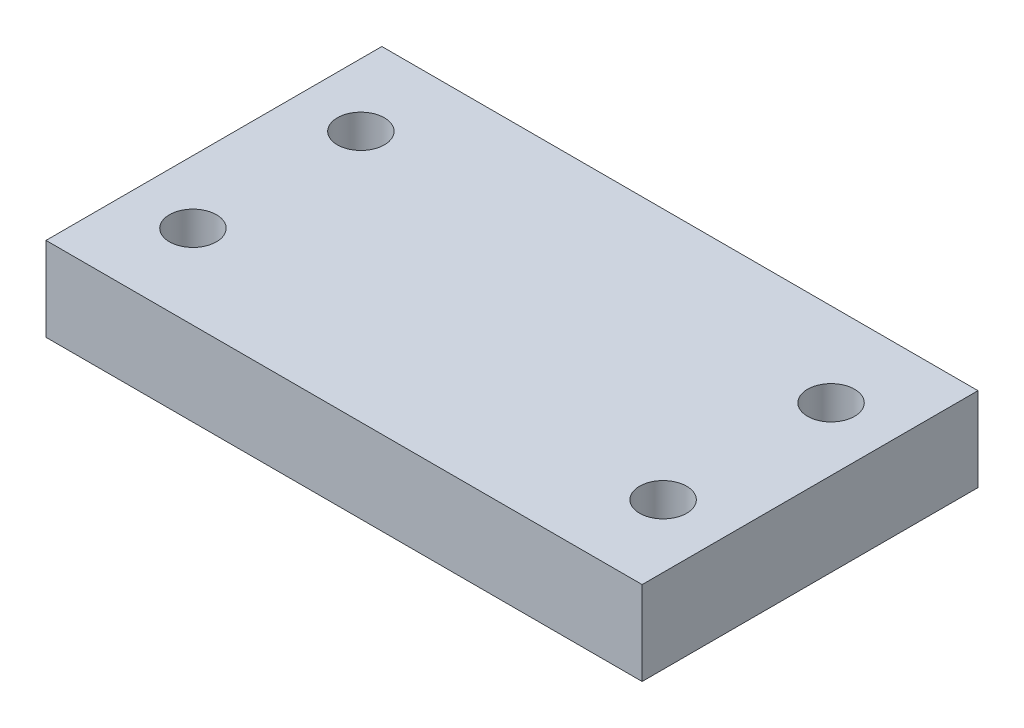
SolidWorks part; units mm, degrees
ref_plane "Front Plane" through (0, 0, 0) normal (0, 0, 1) x (1, 0, 0)
ref_plane "Top Plane" through (0, 0, 0) normal (0, 1, 0) x (1, 0, 0)
ref_plane "Right Plane" through (0, 0, 0) normal (1, 0, 0) x (0, 0, -1)
sketch "Sketch1" plane through (0, 0, 0) normal (0, 1, 0) x (1, 0, 0)
  line L0 (0, -55) -> (0, 55) construction
  line L2 (-35.5, -10) -> (-35.5, 10)
  line L4 (35.5, -10) -> (35.5, 10)
  line L5 (-35.5, -10) -> (35.5, 10) construction
  line L6 (-35.5, 10) -> (35.5, -10) construction
  line L7 (-35.5, -10) -> (35.5, -10)
  line L12 (-35.5, 10) -> (-35.5, 30)
  line L13 (-35.5, 30) -> (35.5, 30)
  line L15 (35.5, 30) -> (35.5, 10)
  circle A0 centre (28, 0) radius 2.8
  circle A1 centre (-28, 0) radius 2.8
  circle A4 centre (-28, 20) radius 2.8
  circle A5 centre (28, 20) radius 2.8
  point P0 (0, 0)
  dimension "D3" = 5.6
  dimension "D1" = 71
  dimension "D2" = 20
  dimension "D4" = 7.5
  dimension "D5" = 0
  dimension "D6" = 20
  dimension "D7" = 10
  dimension "D8" = 2
extrude "Boss-Extrude1" add sketch "Sketch1" along normal blind 10
